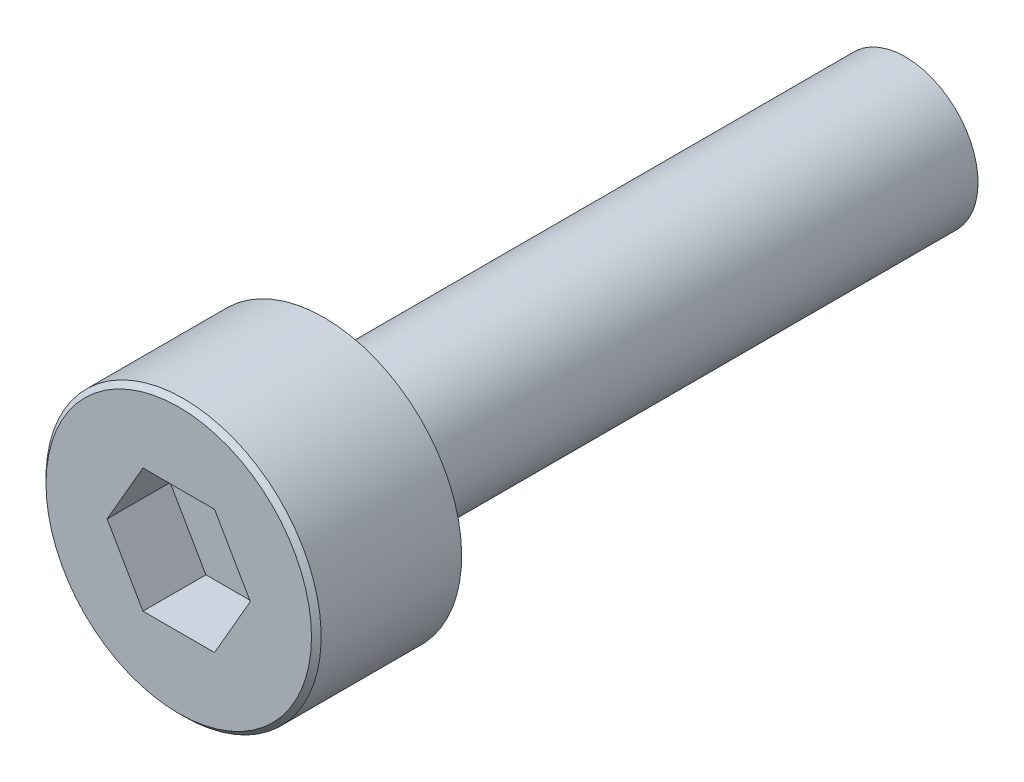
SolidWorks part; units mm, degrees
material "普通碳钢"
ref_plane "前视基准面" through (0, 0, 0) normal (0, 0, 1) x (1, 0, 0)
ref_plane "上视基准面" through (0, 0, 0) normal (0, 1, 0) x (1, 0, 0)
ref_plane "右视基准面" through (0, 0, 0) normal (1, 0, 0) x (0, 0, -1)
sketch "草图1" plane through (0, 0, 0) normal (1, 0, 0) x (0, 0, -1)
  line L0 (0, 0) -> (0, 2.84)
  line L1 (0, 2.84) -> (3, 2.84)
  line L2 (3, 2.84) -> (3, 1.5)
  line L3 (3, 1.5) -> (15, 1.5)
  line L4 (15, 1.5) -> (15, 0)
  line L5 (15, 0) -> (0, 0) construction
  line L6 (0, 0) -> (15, 0)
  dimension "D1" = 5.68
  dimension "D2" = 3
  dimension "D3" = 3
  dimension "D4" = 12
revolve "旋转1" add sketch "草图1" angle 360 about L5
cosmetic thread "装饰螺纹线1" parameters "D2"=2.459
sketch "草图2" plane through (0, 0, 0) normal (0, 0, 1) x (1, 0, 0)
  line L1 (0.739, 1.28) -> (-0.739, 1.28)
  line L2 (-0.739, 1.28) -> (-1.478, 0)
  line L3 (-1.478, 0) -> (-0.739, -1.28)
  line L4 (-0.739, -1.28) -> (0.739, -1.28)
  line L5 (0.739, -1.28) -> (1.478, 0)
  line L6 (1.478, 0) -> (0.739, 1.28)
  circle A0 centre (0, 0) radius 1.28 construction
  dimension "D1" = 2.56
extrude "切除-拉伸1" cut sketch "草图2" against normal blind 1.3
chamfer "装饰倒角" distance 0.1 angle 45 1 edges at (0, 2.84, 0)
